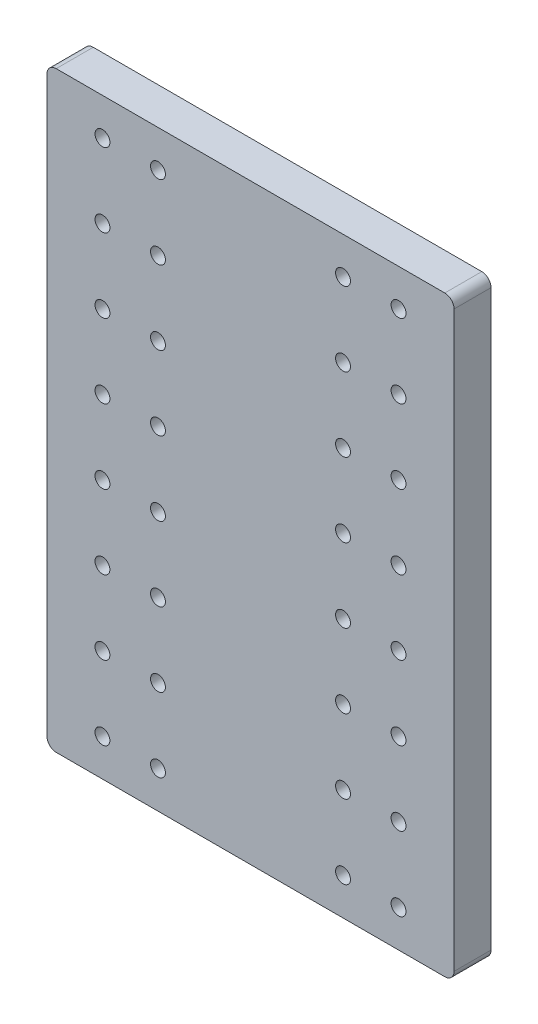
SolidWorks part; units mm, degrees
ref_plane "Front Plane" through (0, 0, 0) normal (0, 0, 1) x (1, 0, 0)
ref_plane "Top Plane" through (0, 0, 0) normal (0, 1, 0) x (1, 0, 0)
ref_plane "Right Plane" through (0, 0, 0) normal (1, 0, 0) x (0, 0, -1)
sketch "Model" plane through (0, 0, 0) normal (0, 0, 1) x (1, 0, 0)
  line L0 (610.5082, 372.2176) -> (470.8082, 372.2176)
  line L1 (610.5082, 575.4176) -> (470.8082, 575.4176)
  line L2 (470.8082, 575.4176) -> (470.8082, 372.2176)
  line L3 (610.5082, 575.4176) -> (610.5082, 372.2176)
  line L4 (489.8582, 562.7176) -> (489.8582, 537.3176) construction
  line L5 (489.8582, 537.3176) -> (489.8582, 511.9176) construction
  line L6 (489.8582, 511.9176) -> (489.8582, 486.5176) construction
  line L7 (489.8582, 486.5176) -> (489.8582, 461.1176) construction
  line L8 (489.8582, 461.1176) -> (489.8582, 435.7176) construction
  line L9 (489.8582, 435.7176) -> (489.8582, 410.3176) construction
  line L10 (489.8582, 410.3176) -> (489.8582, 384.9176) construction
  line L11 (508.9082, 562.7176) -> (508.9082, 537.3176) construction
  line L12 (508.9082, 537.3176) -> (508.9082, 511.9176) construction
  line L13 (508.9082, 511.9176) -> (508.9082, 486.5176) construction
  line L14 (508.9082, 486.5176) -> (508.9082, 461.1176) construction
  line L15 (508.9082, 461.1176) -> (508.9082, 435.7176) construction
  line L16 (508.9082, 435.7176) -> (508.9082, 410.3176) construction
  line L17 (508.9082, 410.3176) -> (508.9082, 384.9176) construction
  line L18 (591.4582, 562.7176) -> (591.4582, 537.3176) construction
  line L19 (591.4582, 537.3176) -> (591.4582, 511.9176) construction
  line L20 (591.4582, 511.9176) -> (591.4582, 486.5176) construction
  line L21 (591.4582, 486.5176) -> (591.4582, 461.1176) construction
  line L22 (591.4582, 461.1176) -> (591.4582, 435.7176) construction
  line L23 (591.4582, 435.7176) -> (591.4582, 410.3176) construction
  line L24 (591.4582, 410.3176) -> (591.4582, 384.9176) construction
  line L25 (572.4082, 384.9176) -> (572.4082, 410.3176) construction
  line L26 (572.4082, 410.3176) -> (572.4082, 435.7176) construction
  line L27 (572.4082, 435.7176) -> (572.4082, 461.1176) construction
  line L28 (572.4082, 461.1176) -> (572.4082, 486.5176) construction
  line L29 (572.4082, 486.5176) -> (572.4082, 511.9176) construction
  line L30 (572.4082, 511.9176) -> (572.4082, 537.3176) construction
  line L31 (572.4082, 537.3176) -> (572.4082, 562.7176) construction
  circle A0 centre (591.4582, 562.7176) radius 2.5527
  circle A1 centre (591.4582, 486.5176) radius 2.5527
  circle A2 centre (489.8582, 486.5176) radius 2.5527
  circle A3 centre (489.8582, 562.7176) radius 2.5527
  circle A4 centre (591.4582, 537.3176) radius 2.5527
  circle A5 centre (489.8582, 537.3176) radius 2.5527
  circle A6 centre (591.4582, 511.9176) radius 2.5527
  circle A7 centre (489.8582, 511.9176) radius 2.5527
  circle A8 centre (508.9082, 486.5176) radius 2.5527
  circle A9 centre (508.9082, 562.7176) radius 2.5527
  circle A10 centre (508.9082, 537.3176) radius 2.5527
  circle A11 centre (508.9082, 511.9176) radius 2.5527
  circle A12 centre (572.4082, 562.7176) radius 2.5527
  circle A13 centre (572.4082, 486.5176) radius 2.5527
  circle A14 centre (572.4082, 537.3176) radius 2.5527
  circle A15 centre (572.4082, 511.9176) radius 2.5527
  circle A16 centre (591.4582, 410.3176) radius 2.5527
  circle A17 centre (489.8582, 410.3176) radius 2.5527
  circle A18 centre (591.4582, 435.7176) radius 2.5527
  circle A19 centre (489.8582, 435.7176) radius 2.5527
  circle A20 centre (508.9082, 410.3176) radius 2.5527
  circle A21 centre (508.9082, 435.7176) radius 2.5527
  circle A22 centre (572.4082, 410.3176) radius 2.5527
  circle A23 centre (572.4082, 435.7176) radius 2.5527
  circle A24 centre (591.4582, 384.9176) radius 2.5527
  circle A25 centre (489.8582, 384.9176) radius 2.5527
  circle A26 centre (508.9082, 384.9176) radius 2.5527
  circle A27 centre (572.4082, 384.9176) radius 2.5527
  circle A28 centre (591.4582, 461.1176) radius 2.5527
  circle A29 centre (489.8582, 461.1176) radius 2.5527
  circle A30 centre (508.9082, 461.1176) radius 2.5527
  circle A31 centre (572.4082, 461.1176) radius 2.5527
  dimension "D1" = 63.5
  dimension "D2" = 19.05
  dimension "D3" = 19.05
  dimension "D4" = 139.7
  dimension "D5" = 19.05
extrude "Boss-Extrude1" add sketch "Model" along normal blind 12.7
fillet "Fillet1" radius 3.175 4 edges at (470.8082, 575.4176, 6.35) (470.8082, 372.2176, 6.35) (610.5082, 372.2176, 6.35) (610.5082, 575.4176, 6.35)
